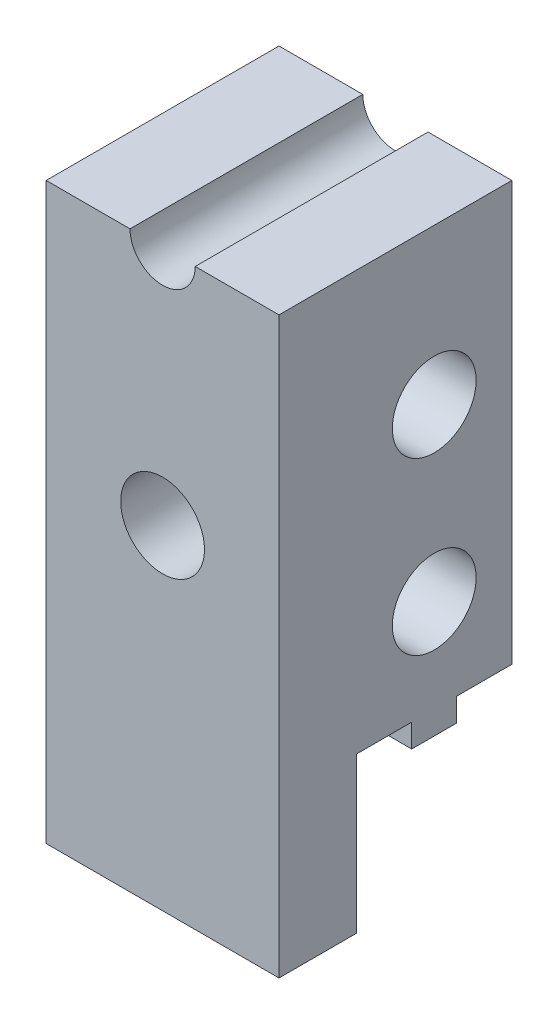
SolidWorks part; units mm, degrees
ref_plane "Front Plane" through (0, 0, 0) normal (0, 0, 1) x (1, 0, 0)
ref_plane "Top Plane" through (0, 0, 0) normal (0, 1, 0) x (1, 0, 0)
ref_plane "Right Plane" through (0, 0, 0) normal (1, 0, 0) x (0, 0, -1)
sketch "Sketch24" plane through (0, 0, 0) normal (1, 0, 0) x (0, 0, -1)
  line L0 (10, -9.1579) -> (10, 44.8421)
  line L1 (2.9, -9.1579) -> (2.9, -12.1579)
  line L3 (-10, -9.1579) -> (-2.9, -9.1579)
  line L4 (2.9, -12.1579) -> (-2.9, -12.1579)
  line L5 (-2.9, -12.1579) -> (-2.9, -9.1579)
  line L6 (2.9, -9.1579) -> (10, -9.1579)
  line L7 (-20, 44.8421) -> (10, 44.8421)
  line L16 (-10, -9.1579) -> (-10, -29.1579)
  line L17 (-10, -29.1579) -> (-20, -29.1579)
  line L18 (-20, 44.8421) -> (-20, -29.1579)
  circle A0 centre (0, 24.8421) radius 5.4
  circle A1 centre (0, 2.8421) radius 5.4
  dimension "D6" = 10.8
  dimension "D1" = 22
  dimension "D2" = 5.8
  dimension "D3" = 3
  dimension "D4" = 7.1
  dimension "D5" = 54
  dimension "D8" = 12
  dimension "D9" = 10
  dimension "D10" = 20
extrude "Boss-Extrude1" add sketch "Sketch24" along normal blind 30
sketch "Sketch25" plane through (0, 0, 20) normal (0, 0, 1) x (1, 0, 0)
  line L0 (0, 44.8421) -> (0, -29.1579) construction
  line L1 (30, -9.1579) -> (0, -9.1579) construction
  circle A0 centre (15, 13.8421) radius 5.4
  point P10 (15, 13.8421)
  dimension "D1" = 10.8
  dimension "D2" = 23
  dimension "D3" = 15
sketch "Sketch26" plane through (0, 0, -10) normal (0, 0, 1) x (1, 0, 0)
  line L2 (30, -9.1579) -> (0, -9.1579) construction
  line L5 (30, 44.8421) -> (30, -29.1579) construction
  circle A0 centre (15, 44.8421) radius 4.2
  point P11 (15, 44.8421)
  dimension "D2" = 8.4
  dimension "D1" = 54
  dimension "D3" = 15
extrude "rods_slot" cut sketch "Sketch26" along normal through all
extrude "rods-hole" cut sketch "Sketch25" against normal blind 50
